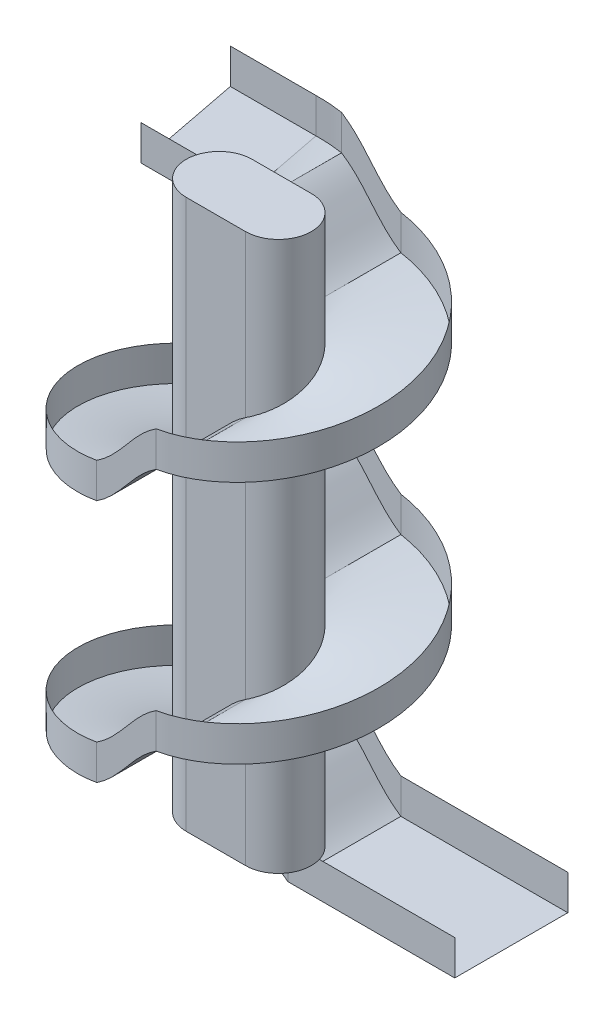
SolidWorks part; units mm, degrees
ref_plane "Front Plane" through (0, 0, 0) normal (0, 0, 1) x (1, 0, 0)
ref_plane "Top Plane" through (0, 0, 0) normal (0, 1, 0) x (1, 0, 0)
ref_plane "Right Plane" through (0, 0, 0) normal (1, 0, 0) x (0, 0, -1)
sketch "Sketch1" plane through (0, 0, 0) normal (0, 1, 0) x (1, 0, 0)
  line L0 (135, 0) -> (-135, 0) construction
  line L1 (135, -150) -> (-135, -150)
  line L2 (135, 150) -> (-135, 150)
  arc A0 (135, -150) -> (135, 150) centre (135, 0) ccw
  arc A1 (-135, 150) -> (-135, -150) centre (-135, 0) ccw
  point P2 (0, 0)
  dimension "D2" = 150
  dimension "D1" = 270
extrude "Boss-Extrude1" add sketch "Sketch1" along normal blind 2500
sketch "Sketch2" plane through (0, 0, 0) normal (0, 1, 0) x (1, 0, 0)
  line L0 (0, 0) -> (208.433, 231.5922)
  point P3 (135, 150)
  point P4 (0, 0)
  point P6 (238.2003, 423.4671)
  point P7 (265.9278, 472.7605)
  point P8 (263.4861, 376.4088)
  point P9 (239.374, 341.9629)
  point P10 (0, 0)
  point P11 (249.6725, 356.675)
  point P12 (247.83, 330.44)
  point P13 (248.2794, 312.6481)
  point P14 (0, 0)
  point P15 (0, 0)
  point P16 (243.7487, 306.9428)
  point P17 (0, 0)
  point P18 (237.7154, 299.3454)
  point P19 (0, 0)
  point P20 (231.8164, 291.917)
  point P21 (221.9692, 279.5168)
  point P22 (189.3881, 238.4887)
  point P23 (199.1628, 250.7976)
  point P24 (208.433, 231.5922)
sketch "Sketch3" plane through (0, 0, 0) normal (0, 0, 1) x (1, 0, 0)
  line L0 (0, 0) -> (0, 2500)
  line L1 (-135, 2500) -> (135, 2500) construction
surface "Surface-Sweep1" parameters "D0"=810
sketch3d "3DSketch1"
  spline S2 degree 3 poles (306.0961, 2771.2923, -1420.1826) (303.4329, 1941.2175, -192.0638) (45.5419, 1783.9163, 168.397) (-154.4548, 1654.0385, 148.8124) (-159.2524, 1650.9168, 148.1057) (-168.7601, 1644.6934, 146.2318) (-173.4702, 1641.5918, 145.0645) (-182.7914, 1635.3918, 142.2662) (-187.4039, 1632.296, 140.6343) (-193.0885, 1628.4007, 138.3012) (-194.2215, 1627.6205, 137.8199) (-196.4793, 1626.0576, 136.8277) (-197.6055, 1625.274, 136.3161) (-200.959, 1622.9277, 134.7424) (-203.1614, 1621.3695, 133.6415) (-209.6688, 1616.7095, 130.1871) (-213.8743, 1613.6221, 127.6821) (-222.0149, 1607.4691, 122.2795) (-225.95, 1604.4034, 119.382) (-233.54, 1598.2778, 113.1982) (-237.1898, 1595.2074, 109.9161) (-242.4361, 1590.5776, 104.707) (-244.1468, 1589.0303, 102.9229) (-247.4896, 1585.9255, 99.2585) (-249.112, 1584.3769, 97.3886) (-253.823, 1579.7491, 91.6811) (-256.7604, 1576.6836, 87.7408) (-262.23, 1570.575, 79.6025) (-264.7631, 1567.5351, 75.4028) (-269.4103, 1561.437, 66.7675) (-271.5254, 1558.3808, 62.3309) (-274.3761, 1553.7736, 55.5012) (-275.2726, 1552.2341, 53.1954) (-276.5349, 1549.9174, 49.6931) (-276.942, 1549.1437, 48.5181) (-277.7247, 1547.6011, 46.1648) (-278.1009, 1546.8311, 44.9852) (-279.9062, 1542.9879, 39.0725) (-281.1092, 1539.9335, 34.2963) (-283.0401, 1533.8488, 24.6629) (-283.767, 1530.8118, 19.8098) (-284.7435, 1524.7215, 10.0479) (-284.9932, 1521.67, 5.138) (-285.0032, 1517.071, -2.2636) (-284.9457, 1515.5343, -4.7369) (-284.7666, 1513.2222, -8.4552) (-284.6914, 1512.4496, -9.6974) (-284.5103, 1510.9082, -12.1737) (-284.4046, 1510.1389, -13.4088) (-284.0422, 1507.8351, -17.1044) (-283.7402, 1506.3045, -19.5555) (-283.0175, 1503.2516, -24.4313) (-282.5967, 1501.7294, -26.8561) (-281.1591, 1497.1615, -34.083) (-279.9672, 1494.1183, -38.8401) (-277.1215, 1488.0205, -48.2235) (-275.4678, 1484.9658, -52.8499) (-272.6374, 1480.363, -59.6828) (-271.6355, 1478.8253, -61.9426) (-270.044, 1476.5118, -65.3042) (-269.4981, 1475.7386, -66.4214) (-268.3802, 1474.1948, -68.6387) (-267.8084, 1473.4244, -69.7386) (-266.0549, 1471.1172, -73.012) (-264.8349, 1469.585, -75.1596) (-262.2978, 1466.5223, -79.381) (-260.9804, 1464.9925, -81.4553) (-256.8845, 1460.4053, -87.5685) (-253.9624, 1457.3497, -91.4981) (-247.744, 1451.2276, -99.0593) (-244.4476, 1448.1612, -102.691) (-239.2228, 1443.5412, -107.9058) (-237.4344, 1441.9977, -109.6052) (-234.6813, 1439.6759, -112.0945) (-233.751, 1438.9001, -112.9149) (-231.8705, 1437.3492, -114.5323) (-230.922, 1436.5748, -115.3277) (-226.1399, 1432.7056, -119.239) (-222.1868, 1429.6211, -122.1572) (-214.0418, 1423.4569, -127.5787) (-209.8498, 1420.3772, -130.082) (-201.2376, 1414.2064, -134.6714) (-196.8174, 1411.1153, -136.7576) (-190.0207, 1406.4576, -139.5662) (-187.7268, 1404.9024, -140.4491) (-183.0876, 1401.7765, -142.1043) (-180.7382, 1400.2035, -142.8778) (-173.6688, 1395.4959, -145.0137) (-168.9139, 1392.3629, -146.1975) (-159.3329, 1386.0902, -148.0937) (-154.5068, 1382.9507, -148.8062) (-147.2229, 1378.2232, -149.5211) (-144.7875, 1376.6443, -149.7003) (12.975, 1274.385, -157.4349) (197.8532, 1159.9741, 75.6966) (-469.0887, -358.7344, 727.2505) knots -1.229861 -1.229861 -1.229861 -1.229861 0.03125 0.03125 0.0625 0.0625 0.09375 0.09375 0.125 0.125 0.132813 0.132813 0.140625 0.140625 0.15625 0.15625 0.1875 0.1875 0.21875 0.21875 0.25 0.25 0.265625 0.265625 0.28125 0.28125 0.3125 0.3125 0.34375 0.34375 0.375 0.375 0.390625 0.390625 0.398438 0.398438 0.40625 0.40625 0.4375 0.4375 0.46875 0.46875 0.5 0.5 0.515625 0.515625 0.523438 0.523438 0.53125 0.53125 0.546875 0.546875 0.5625 0.5625 0.59375 0.59375 0.625 0.625 0.640625 0.640625 0.648438 0.648438 0.65625 0.65625 0.671875 0.671875 0.6875 0.6875 0.71875 0.71875 0.75 0.75 0.765625 0.765625 0.773438 0.773438 0.78125 0.78125 0.8125 0.8125 0.84375 0.84375 0.875 0.875 0.890625 0.890625 0.90625 0.90625 0.9375 0.9375 0.96875 0.96875 0.984375 0.984375 1.978083 1.978083 1.978083 1.978083 only from (-135, 1666.6667, 150) to (-135, 1370.2966, -150)
  spline S3 degree 3 poles (306.0961, 1660.1812, -1420.1826) (303.4329, 830.1063, -192.0638) (45.5419, 672.8052, 168.397) (-154.4548, 542.9274, 148.8124) (-159.2524, 539.8057, 148.1057) (-168.7601, 533.5823, 146.2318) (-173.4702, 530.4807, 145.0645) (-182.7914, 524.2807, 142.2662) (-187.4039, 521.1849, 140.6343) (-193.0885, 517.2896, 138.3012) (-194.2215, 516.5094, 137.8199) (-196.4793, 514.9465, 136.8277) (-197.6055, 514.1629, 136.3161) (-200.959, 511.8166, 134.7424) (-203.1614, 510.2584, 133.6415) (-209.6688, 505.5983, 130.1871) (-213.8743, 502.511, 127.6821) (-222.0149, 496.3579, 122.2795) (-225.95, 493.2923, 119.382) (-233.54, 487.1667, 113.1982) (-237.1898, 484.0963, 109.9161) (-242.4361, 479.4665, 104.707) (-244.1468, 477.9192, 102.9229) (-247.4896, 474.8144, 99.2585) (-249.112, 473.2658, 97.3886) (-253.823, 468.638, 91.6811) (-256.7604, 465.5724, 87.7408) (-262.23, 459.4639, 79.6025) (-264.7631, 456.424, 75.4028) (-269.4103, 450.3259, 66.7675) (-271.5254, 447.2697, 62.3309) (-274.3761, 442.6625, 55.5012) (-275.2726, 441.123, 53.1954) (-276.5349, 438.8063, 49.6931) (-276.942, 438.0326, 48.5181) (-277.7247, 436.49, 46.1648) (-278.1009, 435.72, 44.9852) (-279.9062, 431.8768, 39.0725) (-281.1092, 428.8224, 34.2963) (-283.0401, 422.7376, 24.6629) (-283.767, 419.7007, 19.8098) (-284.7435, 413.6104, 10.0479) (-284.9932, 410.5589, 5.138) (-285.0032, 405.9598, -2.2636) (-284.9457, 404.4232, -4.7369) (-284.7666, 402.1111, -8.4552) (-284.6914, 401.3385, -9.6974) (-284.5103, 399.7971, -12.1737) (-284.4046, 399.0278, -13.4088) (-284.0422, 396.724, -17.1044) (-283.7402, 395.1934, -19.5555) (-283.0175, 392.1405, -24.4313) (-282.5967, 390.6182, -26.8561) (-281.1591, 386.0503, -34.083) (-279.9672, 383.0072, -38.8401) (-277.1215, 376.9094, -48.2235) (-275.4678, 373.8547, -52.8499) (-272.6374, 369.2519, -59.6828) (-271.6355, 367.7142, -61.9426) (-270.044, 365.4007, -65.3042) (-269.4981, 364.6275, -66.4214) (-268.3802, 363.0837, -68.6387) (-267.8084, 362.3133, -69.7386) (-266.0549, 360.0061, -73.012) (-264.8349, 358.4739, -75.1596) (-262.2978, 355.4111, -79.381) (-260.9804, 353.8814, -81.4553) (-256.8845, 349.2942, -87.5685) (-253.9624, 346.2386, -91.4981) (-247.744, 340.1165, -99.0593) (-244.4476, 337.0501, -102.691) (-239.2228, 332.43, -107.9058) (-237.4344, 330.8866, -109.6052) (-234.6813, 328.5648, -112.0945) (-233.751, 327.789, -112.9149) (-231.8705, 326.2381, -114.5323) (-230.922, 325.4637, -115.3277) (-226.1399, 321.5945, -119.239) (-222.1868, 318.51, -122.1572) (-214.0418, 312.3458, -127.5787) (-209.8498, 309.2661, -130.082) (-201.2376, 303.0953, -134.6714) (-196.8174, 300.0042, -136.7576) (-190.0207, 295.3465, -139.5662) (-187.7268, 293.7913, -140.4491) (-183.0876, 290.6653, -142.1043) (-180.7382, 289.0924, -142.8778) (-173.6688, 284.3848, -145.0137) (-168.9139, 281.2518, -146.1975) (-159.3329, 274.9791, -148.0937) (-154.5068, 271.8395, -148.8062) (-147.2229, 267.112, -149.5211) (-144.7875, 265.5332, -149.7003) (12.975, 163.2739, -157.4349) (197.8532, 48.863, 75.6966) (-469.0887, -1469.8455, 727.2505) knots -1.229861 -1.229861 -1.229861 -1.229861 0.03125 0.03125 0.0625 0.0625 0.09375 0.09375 0.125 0.125 0.132813 0.132813 0.140625 0.140625 0.15625 0.15625 0.1875 0.1875 0.21875 0.21875 0.25 0.25 0.265625 0.265625 0.28125 0.28125 0.3125 0.3125 0.34375 0.34375 0.375 0.375 0.390625 0.390625 0.398438 0.398438 0.40625 0.40625 0.4375 0.4375 0.46875 0.46875 0.5 0.5 0.515625 0.515625 0.523438 0.523438 0.53125 0.53125 0.546875 0.546875 0.5625 0.5625 0.59375 0.59375 0.625 0.625 0.640625 0.640625 0.648438 0.648438 0.65625 0.65625 0.671875 0.671875 0.6875 0.6875 0.71875 0.71875 0.75 0.75 0.765625 0.765625 0.773438 0.773438 0.78125 0.78125 0.8125 0.8125 0.84375 0.84375 0.875 0.875 0.890625 0.890625 0.90625 0.90625 0.9375 0.9375 0.96875 0.96875 0.984375 0.984375 1.978083 1.978083 1.978083 1.978083 only from (-135, 555.5556, 150) to (-135, 259.1855, -150)
  spline S4 degree 3 poles (-540.0805, 726.5593, 641.2477) (189.7951, 2276.0753, 80.1304) (14.3209, 2384.6243, -157.3391) (-144.5844, 2487.6238, -149.7127) (-146.974, 2489.1729, -149.5405) (-360.4381, 2627.7053, -129.012) (-535.1485, 2754.3772, 338.8163) (-179.6878, 3597.1923, 1479.3575) knots -16.096892 -16.096892 -16.096892 -16.096892 0.25 0.25 0.5 0.5 22.625823 22.625823 22.625823 22.625823 only from (-135, 2481.4077, -150) to (-163.6075, 2500, -147.2468)
  spline S5 degree 3 poles (-135, 2481.4077, -150) (-137.3992, 2482.9676, -150) (-139.7972, 2484.5208, -149.9424) (-144.5844, 2487.6238, -149.7127) (-146.974, 2489.1729, -149.5405) (-154.129, 2493.8162, -148.8524) (-158.8804, 2496.9066, -148.1652) (-163.6075, 2500, -147.2468) knots 0 0 0 0 0.25 0.25 0.5 0.5 1 1 1 1
  spline S6 degree 3 poles (-135, 555.5556, 150) (-139.9082, 552.3677, 150) (-144.7828, 549.2084, 149.7595) (-154.4548, 542.9274, 148.8124) (-159.2524, 539.8057, 148.1057) (-168.7601, 533.5823, 146.2318) (-173.4702, 530.4807, 145.0645) (-182.7914, 524.2807, 142.2662) (-187.4039, 521.1849, 140.6343) (-193.0885, 517.2896, 138.3012) (-194.2215, 516.5094, 137.8199) (-196.4793, 514.9465, 136.8277) (-197.6055, 514.1629, 136.3161) (-200.959, 511.8166, 134.7424) (-203.1614, 510.2584, 133.6415) (-209.6688, 505.5983, 130.1871) (-213.8743, 502.511, 127.6821) (-222.0149, 496.3579, 122.2795) (-225.95, 493.2923, 119.382) (-233.54, 487.1667, 113.1982) (-237.1898, 484.0963, 109.9161) (-242.4361, 479.4665, 104.707) (-244.1468, 477.9192, 102.9229) (-247.4896, 474.8144, 99.2585) (-249.112, 473.2658, 97.3886) (-253.823, 468.638, 91.6811) (-256.7604, 465.5724, 87.7408) (-262.23, 459.4639, 79.6025) (-264.7631, 456.424, 75.4028) (-269.4103, 450.3259, 66.7675) (-271.5254, 447.2697, 62.3309) (-274.3761, 442.6625, 55.5012) (-275.2726, 441.123, 53.1954) (-276.5349, 438.8063, 49.6931) (-276.942, 438.0326, 48.5181) (-277.7247, 436.49, 46.1648) (-278.1009, 435.72, 44.9852) (-279.9062, 431.8768, 39.0725) (-281.1092, 428.8224, 34.2963) (-283.0401, 422.7376, 24.6629) (-283.767, 419.7007, 19.8098) (-284.7435, 413.6104, 10.0479) (-284.9932, 410.5589, 5.138) (-285.0032, 405.9598, -2.2636) (-284.9457, 404.4232, -4.7369) (-284.7666, 402.1111, -8.4552) (-284.6914, 401.3385, -9.6974) (-284.5103, 399.7971, -12.1737) (-284.4046, 399.0278, -13.4088) (-284.0422, 396.724, -17.1044) (-283.7402, 395.1934, -19.5555) (-283.0175, 392.1405, -24.4313) (-282.5967, 390.6182, -26.8561) (-281.1591, 386.0503, -34.083) (-279.9672, 383.0072, -38.8401) (-277.1215, 376.9094, -48.2235) (-275.4678, 373.8547, -52.8499) (-272.6374, 369.2519, -59.6828) (-271.6355, 367.7142, -61.9426) (-270.044, 365.4007, -65.3042) (-269.4981, 364.6275, -66.4214) (-268.3802, 363.0837, -68.6387) (-267.8084, 362.3133, -69.7386) (-266.0549, 360.0061, -73.012) (-264.8349, 358.4739, -75.1596) (-262.2978, 355.4111, -79.381) (-260.9804, 353.8814, -81.4553) (-256.8845, 349.2942, -87.5685) (-253.9624, 346.2386, -91.4981) (-247.744, 340.1165, -99.0593) (-244.4476, 337.0501, -102.691) (-239.2228, 332.43, -107.9058) (-237.4344, 330.8866, -109.6052) (-234.6813, 328.5648, -112.0945) (-233.751, 327.789, -112.9149) (-231.8705, 326.2381, -114.5323) (-230.922, 325.4637, -115.3277) (-226.1399, 321.5945, -119.239) (-222.1868, 318.51, -122.1572) (-214.0418, 312.3458, -127.5787) (-209.8498, 309.2661, -130.082) (-201.2376, 303.0953, -134.6714) (-196.8174, 300.0042, -136.7576) (-190.0207, 295.3465, -139.5662) (-187.7268, 293.7913, -140.4491) (-183.0876, 290.6653, -142.1043) (-180.7382, 289.0924, -142.8778) (-173.6688, 284.3848, -145.0137) (-168.9139, 281.2518, -146.1975) (-159.3329, 274.9791, -148.0937) (-154.5068, 271.8395, -148.8062) (-147.2229, 267.112, -149.5211) (-144.7875, 265.5332, -149.7003) (-139.903, 262.3671, -149.9398) (-137.4534, 260.7807, -150) (-135, 259.1855, -150) knots 0 0 0 0 0.03125 0.03125 0.0625 0.0625 0.09375 0.09375 0.125 0.125 0.132813 0.132813 0.140625 0.140625 0.15625 0.15625 0.1875 0.1875 0.21875 0.21875 0.25 0.25 0.265625 0.265625 0.28125 0.28125 0.3125 0.3125 0.34375 0.34375 0.375 0.375 0.390625 0.390625 0.398438 0.398438 0.40625 0.40625 0.4375 0.4375 0.46875 0.46875 0.5 0.5 0.515625 0.515625 0.523438 0.523438 0.53125 0.53125 0.546875 0.546875 0.5625 0.5625 0.59375 0.59375 0.625 0.625 0.640625 0.640625 0.648438 0.648438 0.65625 0.65625 0.671875 0.671875 0.6875 0.6875 0.71875 0.71875 0.75 0.75 0.765625 0.765625 0.773438 0.773438 0.78125 0.78125 0.8125 0.8125 0.84375 0.84375 0.875 0.875 0.890625 0.890625 0.90625 0.90625 0.9375 0.9375 0.96875 0.96875 0.984375 0.984375 1 1 1 1
  spline S7 degree 3 poles (-135, 1666.6667, 150) (-139.9082, 1663.4788, 150) (-144.7828, 1660.3196, 149.7595) (-154.4548, 1654.0385, 148.8124) (-159.2524, 1650.9168, 148.1057) (-168.7601, 1644.6934, 146.2318) (-173.4702, 1641.5918, 145.0645) (-182.7914, 1635.3918, 142.2662) (-187.4039, 1632.296, 140.6343) (-193.0885, 1628.4007, 138.3012) (-194.2215, 1627.6205, 137.8199) (-196.4793, 1626.0576, 136.8277) (-197.6055, 1625.274, 136.3161) (-200.959, 1622.9277, 134.7424) (-203.1614, 1621.3695, 133.6415) (-209.6688, 1616.7095, 130.1871) (-213.8743, 1613.6221, 127.6821) (-222.0149, 1607.4691, 122.2795) (-225.95, 1604.4034, 119.382) (-233.54, 1598.2778, 113.1982) (-237.1898, 1595.2074, 109.9161) (-242.4361, 1590.5776, 104.707) (-244.1468, 1589.0303, 102.9229) (-247.4896, 1585.9255, 99.2585) (-249.112, 1584.3769, 97.3886) (-253.823, 1579.7491, 91.6811) (-256.7604, 1576.6836, 87.7408) (-262.23, 1570.575, 79.6025) (-264.7631, 1567.5351, 75.4028) (-269.4103, 1561.437, 66.7675) (-271.5254, 1558.3808, 62.3309) (-274.3761, 1553.7736, 55.5012) (-275.2726, 1552.2341, 53.1954) (-276.5349, 1549.9174, 49.6931) (-276.942, 1549.1437, 48.5181) (-277.7247, 1547.6011, 46.1648) (-278.1009, 1546.8311, 44.9852) (-279.9062, 1542.9879, 39.0725) (-281.1092, 1539.9335, 34.2963) (-283.0401, 1533.8488, 24.6629) (-283.767, 1530.8118, 19.8098) (-284.7435, 1524.7215, 10.0479) (-284.9932, 1521.67, 5.138) (-285.0032, 1517.071, -2.2636) (-284.9457, 1515.5343, -4.7369) (-284.7666, 1513.2222, -8.4552) (-284.6914, 1512.4496, -9.6974) (-284.5103, 1510.9082, -12.1737) (-284.4046, 1510.1389, -13.4088) (-284.0422, 1507.8351, -17.1044) (-283.7402, 1506.3045, -19.5555) (-283.0175, 1503.2516, -24.4313) (-282.5967, 1501.7294, -26.8561) (-281.1591, 1497.1615, -34.083) (-279.9672, 1494.1183, -38.8401) (-277.1215, 1488.0205, -48.2235) (-275.4678, 1484.9658, -52.8499) (-272.6374, 1480.363, -59.6828) (-271.6355, 1478.8253, -61.9426) (-270.044, 1476.5118, -65.3042) (-269.4981, 1475.7386, -66.4214) (-268.3802, 1474.1948, -68.6387) (-267.8084, 1473.4244, -69.7386) (-266.0549, 1471.1172, -73.012) (-264.8349, 1469.585, -75.1596) (-262.2978, 1466.5223, -79.381) (-260.9804, 1464.9925, -81.4553) (-256.8845, 1460.4053, -87.5685) (-253.9624, 1457.3497, -91.4981) (-247.744, 1451.2276, -99.0593) (-244.4476, 1448.1612, -102.691) (-239.2228, 1443.5412, -107.9058) (-237.4344, 1441.9977, -109.6052) (-234.6813, 1439.6759, -112.0945) (-233.751, 1438.9001, -112.9149) (-231.8705, 1437.3492, -114.5323) (-230.922, 1436.5748, -115.3277) (-226.1399, 1432.7056, -119.239) (-222.1868, 1429.6211, -122.1572) (-214.0418, 1423.4569, -127.5787) (-209.8498, 1420.3772, -130.082) (-201.2376, 1414.2064, -134.6714) (-196.8174, 1411.1153, -136.7576) (-190.0207, 1406.4576, -139.5662) (-187.7268, 1404.9024, -140.4491) (-183.0876, 1401.7765, -142.1043) (-180.7382, 1400.2035, -142.8778) (-173.6688, 1395.4959, -145.0137) (-168.9139, 1392.3629, -146.1975) (-159.3329, 1386.0902, -148.0937) (-154.5068, 1382.9507, -148.8062) (-147.2229, 1378.2232, -149.5211) (-144.7875, 1376.6443, -149.7003) (-139.903, 1373.4782, -149.9398) (-137.4534, 1371.8918, -150) (-135, 1370.2966, -150) knots 0 0 0 0 0.03125 0.03125 0.0625 0.0625 0.09375 0.09375 0.125 0.125 0.132813 0.132813 0.140625 0.140625 0.15625 0.15625 0.1875 0.1875 0.21875 0.21875 0.25 0.25 0.265625 0.265625 0.28125 0.28125 0.3125 0.3125 0.34375 0.34375 0.375 0.375 0.390625 0.390625 0.398438 0.398438 0.40625 0.40625 0.4375 0.4375 0.46875 0.46875 0.5 0.5 0.515625 0.515625 0.523438 0.523438 0.53125 0.53125 0.546875 0.546875 0.5625 0.5625 0.59375 0.59375 0.625 0.625 0.640625 0.640625 0.648438 0.648438 0.65625 0.65625 0.671875 0.671875 0.6875 0.6875 0.71875 0.71875 0.75 0.75 0.765625 0.765625 0.773438 0.773438 0.78125 0.78125 0.8125 0.8125 0.84375 0.84375 0.875 0.875 0.890625 0.890625 0.90625 0.90625 0.9375 0.9375 0.96875 0.96875 0.984375 0.984375 1 1 1 1
  spline S10 degree 3 poles (-135, 2481.4077, -150) (-128.353, 2477.0858, -150) (-121.882, 2472.579, -150) (-109.2606, 2463.2287, -150) (-103.1101, 2458.3854, -150) (-94.0902, 2450.9042, -150) (-91.1179, 2448.3744, -150) (-85.2489, 2443.2354, -150) (-82.3505, 2440.628, -150) (-73.7524, 2432.7038, -150) (-68.15, 2427.2848, -150) (-59.8911, 2419.0044, -150) (-57.1614, 2416.2199, -150) (-51.7563, 2410.5936, -150) (-49.0793, 2407.7538, -150) (-41.1102, 2399.1691, -150) (-35.8805, 2393.3586, -150) (-28.102, 2384.5738, -150) (-25.5219, 2381.6322, -150) (-20.3894, 2375.7197, -150) (-15.2811, 2369.7819, -150) (-10.2007, 2363.8147, -150) (-5.1241, 2357.8436, -150) (-2.5864, 2354.8574, -150) (5.0286, 2345.9006, -150) (10.0933, 2339.9172, -150) (17.7349, 2330.988, -150) (20.2895, 2328.0193, -150) (25.4238, 2322.1078, -150) (28.0053, 2319.167, -150) (35.7803, 2310.3758, -150) (41.0094, 2304.5622, -150) (48.9808, 2295.9741, -150) (51.6592, 2293.1334, -150) (57.068, 2287.5058, -150) (59.7984, 2284.7187, -150) (68.0573, 2276.4279, -150) (73.6619, 2271.0027, -150) (82.2676, 2263.0703, -150) (85.1692, 2260.4604, -150) (91.046, 2255.3166, -150) (94.0218, 2252.7834, -150) (103.0486, 2245.2866, -150) (109.2067, 2240.4336, -150) (121.8498, 2231.0658, -150) (128.335, 2226.551, -150) (135, 2222.2222, -150) knots 0 0 0 0 0.0625 0.0625 0.125 0.125 0.15625 0.15625 0.1875 0.1875 0.25 0.25 0.28125 0.28125 0.3125 0.3125 0.375 0.375 0.40625 0.40625 0.4375 0.46875 0.46875 0.5 0.5 0.5625 0.5625 0.59375 0.59375 0.625 0.625 0.6875 0.6875 0.71875 0.71875 0.75 0.75 0.8125 0.8125 0.84375 0.84375 0.875 0.875 0.9375 0.9375 1 1 1 1
  spline S11 degree 3 poles (-135, 1370.2966, -150) (-128.353, 1365.9747, -150) (-121.882, 1361.4678, -150) (-109.2606, 1352.1176, -150) (-103.1101, 1347.2743, -150) (-94.0902, 1339.793, -150) (-91.1179, 1337.2633, -150) (-85.2489, 1332.1242, -150) (-82.3505, 1329.5168, -150) (-73.7524, 1321.5927, -150) (-68.15, 1316.1737, -150) (-59.8911, 1307.8933, -150) (-57.1614, 1305.1088, -150) (-51.7563, 1299.4825, -150) (-49.0793, 1296.6427, -150) (-41.1102, 1288.0579, -150) (-35.8805, 1282.2475, -150) (-28.102, 1273.4627, -150) (-25.5219, 1270.521, -150) (-20.3894, 1264.6086, -150) (-15.2811, 1258.6708, -150) (-10.2007, 1252.7035, -150) (-5.1241, 1246.7325, -150) (-2.5864, 1243.7463, -150) (5.0286, 1234.7895, -150) (10.0933, 1228.8061, -150) (17.7349, 1219.8769, -150) (20.2895, 1216.9082, -150) (25.4238, 1210.9967, -150) (28.0053, 1208.0559, -150) (35.7803, 1199.2646, -150) (41.0094, 1193.4511, -150) (48.9808, 1184.863, -150) (51.6592, 1182.0223, -150) (57.068, 1176.3947, -150) (59.7984, 1173.6076, -150) (68.0573, 1165.3168, -150) (73.6619, 1159.8916, -150) (82.2676, 1151.9592, -150) (85.1692, 1149.3493, -150) (91.046, 1144.2055, -150) (94.0218, 1141.6723, -150) (103.0486, 1134.1755, -150) (109.2067, 1129.3225, -150) (121.8498, 1119.9547, -150) (128.335, 1115.4399, -150) (135, 1111.1111, -150) knots 0 0 0 0 0.0625 0.0625 0.125 0.125 0.15625 0.15625 0.1875 0.1875 0.25 0.25 0.28125 0.28125 0.3125 0.3125 0.375 0.375 0.40625 0.40625 0.4375 0.46875 0.46875 0.5 0.5 0.5625 0.5625 0.59375 0.59375 0.625 0.625 0.6875 0.6875 0.71875 0.71875 0.75 0.75 0.8125 0.8125 0.84375 0.84375 0.875 0.875 0.9375 0.9375 1 1 1 1
  spline S12 degree 3 poles (-135, 259.1855, -150) (-128.353, 254.8636, -150) (-121.882, 250.3567, -150) (-109.2606, 241.0065, -150) (-103.1101, 236.1632, -150) (-94.0902, 228.6819, -150) (-91.1179, 226.1522, -150) (-85.2489, 221.0131, -150) (-82.3505, 218.4057, -150) (-73.7524, 210.4816, -150) (-68.15, 205.0626, -150) (-59.8911, 196.7822, -150) (-57.1614, 193.9977, -150) (-51.7563, 188.3714, -150) (-49.0793, 185.5316, -150) (-41.1102, 176.9468, -150) (-35.8805, 171.1364, -150) (-28.102, 162.3516, -150) (-25.5219, 159.4099, -150) (-20.3894, 153.4975, -150) (-15.2811, 147.5596, -150) (-10.2007, 141.5924, -150) (-5.1241, 135.6213, -150) (-2.5864, 132.6351, -150) (5.0286, 123.6784, -150) (10.0933, 117.695, -150) (17.7349, 108.7658, -150) (20.2895, 105.7971, -150) (25.4238, 99.8856, -150) (28.0053, 96.9447, -150) (35.7803, 88.1535, -150) (41.0094, 82.34, -150) (48.9808, 73.7519, -150) (51.6592, 70.9112, -150) (57.068, 65.2835, -150) (59.7984, 62.4965, -150) (68.0573, 54.2056, -150) (73.6619, 48.7805, -150) (82.2676, 40.8481, -150) (85.1692, 38.2382, -150) (91.046, 33.0944, -150) (94.0218, 30.5612, -150) (103.0486, 23.0644, -150) (109.2067, 18.2114, -150) (121.8498, 8.8436, -150) (128.335, 4.3288, -150) (135, 0, -150) knots 0 0 0 0 0.0625 0.0625 0.125 0.125 0.15625 0.15625 0.1875 0.1875 0.25 0.25 0.28125 0.28125 0.3125 0.3125 0.375 0.375 0.40625 0.40625 0.4375 0.46875 0.46875 0.5 0.5 0.5625 0.5625 0.59375 0.59375 0.625 0.625 0.6875 0.6875 0.71875 0.71875 0.75 0.75 0.8125 0.8125 0.84375 0.84375 0.875 0.875 0.9375 0.9375 1 1 1 1
  spline S13 degree 3 poles (135, 1925.8521, 150) (128.3524, 1921.5299, 150) (121.8809, 1917.0227, 150) (109.2585, 1907.6716, 150) (103.1075, 1902.8278, 150) (94.0869, 1895.3459, 150) (91.1144, 1892.8158, 150) (85.245, 1887.6763, 150) (82.3464, 1885.0687, 150) (73.7477, 1877.1438, 150) (68.1449, 1871.7242, 150) (59.8854, 1863.443, 150) (57.1555, 1860.6582, 150) (51.7501, 1855.0315, 150) (49.0728, 1852.1914, 150) (41.1031, 1843.6058, 150) (35.8731, 1837.7948, 150) (28.094, 1829.0091, 150) (25.5137, 1826.0672, 150) (20.3808, 1820.1542, 150) (15.2721, 1814.2158, 150) (10.1914, 1808.2481, 150) (5.1143, 1802.2765, 150) (2.5763, 1799.29, 150) (-5.0393, 1790.3324, 150) (-10.1037, 1784.3493, 150) (-17.7481, 1775.4171, 150) (-20.3041, 1772.4468, 150) (-25.4432, 1766.5301, 150) (-28.0282, 1763.5854, 150) (-35.8158, 1754.7804, 150) (-41.0568, 1748.9542, 150) (-49.0566, 1740.3377, 150) (-51.7463, 1737.486, 150) (-57.1822, 1731.8328, 150) (-59.9294, 1729.0299, 150) (-68.2332, 1720.6993, 150) (-73.8617, 1715.2567, 150) (-82.4885, 1707.3144, 150) (-85.3948, 1704.7038, 150) (-91.2752, 1699.5642, 150) (-94.2496, 1697.0355, 150) (-103.2639, 1689.5589, 150) (-109.4017, 1684.7288, 150) (-121.9731, 1675.4239, 150) (-128.4065, 1670.9491, 150) (-135, 1666.6667, 150) knots 0 0 0 0 0.0625 0.0625 0.125 0.125 0.15625 0.15625 0.1875 0.1875 0.25 0.25 0.28125 0.28125 0.3125 0.3125 0.375 0.375 0.40625 0.40625 0.4375 0.46875 0.46875 0.5 0.5 0.5625 0.5625 0.59375 0.59375 0.625 0.625 0.6875 0.6875 0.71875 0.71875 0.75 0.75 0.8125 0.8125 0.84375 0.84375 0.875 0.875 0.9375 0.9375 1 1 1 1
  spline S14 degree 3 poles (135, 814.741, 150) (128.3524, 810.4188, 150) (121.8809, 805.9115, 150) (109.2585, 796.5605, 150) (103.1075, 791.7167, 150) (94.0869, 784.2348, 150) (91.1144, 781.7047, 150) (85.245, 776.5652, 150) (82.3464, 773.9576, 150) (73.7477, 766.0326, 150) (68.1449, 760.6131, 150) (59.8854, 752.3319, 150) (57.1555, 749.5471, 150) (51.7501, 743.9203, 150) (49.0728, 741.0803, 150) (41.1031, 732.4947, 150) (35.8731, 726.6837, 150) (28.094, 717.898, 150) (25.5137, 714.9561, 150) (20.3808, 709.0431, 150) (15.2721, 703.1047, 150) (10.1914, 697.137, 150) (5.1143, 691.1654, 150) (2.5763, 688.1789, 150) (-5.0393, 679.2213, 150) (-10.1037, 673.2382, 150) (-17.7481, 664.306, 150) (-20.3041, 661.3357, 150) (-25.4432, 655.4189, 150) (-28.0282, 652.4743, 150) (-35.8158, 643.6693, 150) (-41.0568, 637.8431, 150) (-49.0566, 629.2265, 150) (-51.7463, 626.3748, 150) (-57.1822, 620.7217, 150) (-59.9294, 617.9188, 150) (-68.2332, 609.5882, 150) (-73.8617, 604.1456, 150) (-82.4885, 596.2033, 150) (-85.3948, 593.5927, 150) (-91.2752, 588.4531, 150) (-94.2496, 585.9244, 150) (-103.2639, 578.4477, 150) (-109.4017, 573.6177, 150) (-121.9731, 564.3127, 150) (-128.4065, 559.8379, 150) (-135, 555.5556, 150) knots 0 0 0 0 0.0625 0.0625 0.125 0.125 0.15625 0.15625 0.1875 0.1875 0.25 0.25 0.28125 0.28125 0.3125 0.3125 0.375 0.375 0.40625 0.40625 0.4375 0.46875 0.46875 0.5 0.5 0.5625 0.5625 0.59375 0.59375 0.625 0.625 0.6875 0.6875 0.71875 0.71875 0.75 0.75 0.8125 0.8125 0.84375 0.84375 0.875 0.875 0.9375 0.9375 1 1 1 1
  spline S18 degree 3 poles (-306.0961, 2215.7367, 1420.1826) (-303.4329, 1385.6619, 192.0638) (-45.5419, 1228.3608, -168.397) (154.4548, 1098.483, -148.8124) (159.2524, 1095.3613, -148.1057) (168.7601, 1089.1379, -146.2318) (173.4702, 1086.0362, -145.0645) (182.7914, 1079.8363, -142.2662) (187.4039, 1076.7405, -140.6343) (193.0885, 1072.8451, -138.3012) (194.2215, 1072.0649, -137.8199) (196.4793, 1070.5021, -136.8277) (197.6055, 1069.7184, -136.3161) (200.959, 1067.3721, -134.7424) (203.1614, 1065.814, -133.6415) (209.6688, 1061.1539, -130.1871) (213.8743, 1058.0665, -127.6821) (222.0149, 1051.9135, -122.2795) (225.95, 1048.8479, -119.382) (233.54, 1042.7222, -113.1982) (237.1898, 1039.6518, -109.9161) (242.4361, 1035.0221, -104.707) (244.1468, 1033.4748, -102.9229) (247.4896, 1030.37, -99.2585) (249.112, 1028.8214, -97.3886) (253.823, 1024.1936, -91.6811) (256.7604, 1021.128, -87.7408) (262.23, 1015.0195, -79.6025) (264.7631, 1011.9796, -75.4028) (269.4103, 1005.8814, -66.7675) (271.5254, 1002.8253, -62.3309) (274.3761, 998.2181, -55.5012) (275.2726, 996.6785, -53.1954) (276.5349, 994.3618, -49.6931) (276.942, 993.5882, -48.5181) (277.7247, 992.0455, -46.1648) (278.1009, 991.2756, -44.9852) (279.9062, 987.4323, -39.0725) (281.1092, 984.378, -34.2963) (283.0401, 978.2932, -24.6629) (283.767, 975.2563, -19.8098) (284.7435, 969.166, -10.0479) (284.9932, 966.1145, -5.138) (285.0032, 961.5154, 2.2636) (284.9457, 959.9787, 4.7369) (284.7666, 957.6667, 8.4552) (284.6914, 956.894, 9.6974) (284.5103, 955.3526, 12.1737) (284.4046, 954.5834, 13.4088) (284.0422, 952.2796, 17.1044) (283.7402, 950.749, 19.5555) (283.0175, 947.6961, 24.4313) (282.5967, 946.1738, 26.8561) (281.1591, 941.6059, 34.083) (279.9672, 938.5628, 38.8401) (277.1215, 932.4649, 48.2235) (275.4678, 929.4103, 52.8499) (272.6374, 924.8075, 59.6828) (271.6355, 923.2697, 61.9426) (270.044, 920.9563, 65.3042) (269.4981, 920.183, 66.4214) (268.3802, 918.6393, 68.6387) (267.8084, 917.8689, 69.7386) (266.0549, 915.5617, 73.012) (264.8349, 914.0294, 75.1596) (262.2978, 910.9667, 79.381) (260.9804, 909.437, 81.4553) (256.8845, 904.8497, 87.5685) (253.9624, 901.7941, 91.4981) (247.744, 895.672, 99.0593) (244.4476, 892.6056, 102.691) (239.2228, 887.9856, 107.9058) (237.4344, 886.4422, 109.6052) (234.6813, 884.1203, 112.0945) (233.751, 883.3446, 112.9149) (231.8705, 881.7937, 114.5323) (230.922, 881.0193, 115.3277) (226.1399, 877.1501, 119.239) (222.1868, 874.0656, 122.1572) (214.0418, 867.9013, 127.5787) (209.8498, 864.8217, 130.082) (201.2376, 858.6509, 134.6714) (196.8174, 855.5598, 136.7576) (190.0207, 850.902, 139.5662) (187.7268, 849.3468, 140.4491) (183.0876, 846.2209, 142.1043) (180.7382, 844.648, 142.8778) (173.6688, 839.9403, 145.0137) (168.9139, 836.8073, 146.1975) (159.3329, 830.5347, 148.0937) (154.5068, 827.3951, 148.8062) (147.2229, 822.6676, 149.5211) (144.7875, 821.0887, 149.7003) (-12.975, 718.8294, 157.4349) (-197.8532, 604.4186, -75.6966) (469.0887, -914.2899, -727.2505) knots -1.229861 -1.229861 -1.229861 -1.229861 0.03125 0.03125 0.0625 0.0625 0.09375 0.09375 0.125 0.125 0.132813 0.132813 0.140625 0.140625 0.15625 0.15625 0.1875 0.1875 0.21875 0.21875 0.25 0.25 0.265625 0.265625 0.28125 0.28125 0.3125 0.3125 0.34375 0.34375 0.375 0.375 0.390625 0.390625 0.398437 0.398437 0.40625 0.40625 0.4375 0.4375 0.46875 0.46875 0.5 0.5 0.515625 0.515625 0.523437 0.523437 0.53125 0.53125 0.546875 0.546875 0.5625 0.5625 0.59375 0.59375 0.625 0.625 0.640625 0.640625 0.648437 0.648437 0.65625 0.65625 0.671875 0.671875 0.6875 0.6875 0.71875 0.71875 0.75 0.75 0.765625 0.765625 0.773438 0.773438 0.78125 0.78125 0.8125 0.8125 0.84375 0.84375 0.875 0.875 0.890625 0.890625 0.90625 0.90625 0.9375 0.9375 0.96875 0.96875 0.984375 0.984375 1.978083 1.978083 1.978083 1.978083 only from (135, 1111.1111, -150) to (135, 814.741, 150)
  spline S19 degree 3 poles (-306.0961, 3326.8478, 1420.1826) (-303.4329, 2496.773, 192.0638) (-45.5419, 2339.4719, -168.397) (154.4548, 2209.5941, -148.8124) (159.2524, 2206.4724, -148.1057) (168.7601, 2200.249, -146.2318) (173.4702, 2197.1474, -145.0645) (182.7914, 2190.9474, -142.2662) (187.4039, 2187.8516, -140.6343) (193.0885, 2183.9562, -138.3012) (194.2215, 2183.176, -137.8199) (196.4793, 2181.6132, -136.8277) (197.6055, 2180.8295, -136.3161) (200.959, 2178.4833, -134.7424) (203.1614, 2176.9251, -133.6415) (209.6688, 2172.265, -130.1871) (213.8743, 2169.1776, -127.6821) (222.0149, 2163.0246, -122.2795) (225.95, 2159.959, -119.382) (233.54, 2153.8334, -113.1982) (237.1898, 2150.763, -109.9161) (242.4361, 2146.1332, -104.707) (244.1468, 2144.5859, -102.9229) (247.4896, 2141.4811, -99.2585) (249.112, 2139.9325, -97.3886) (253.823, 2135.3047, -91.6811) (256.7604, 2132.2391, -87.7408) (262.23, 2126.1306, -79.6025) (264.7631, 2123.0907, -75.4028) (269.4103, 2116.9925, -66.7675) (271.5254, 2113.9364, -62.3309) (274.3761, 2109.3292, -55.5012) (275.2726, 2107.7897, -53.1954) (276.5349, 2105.4729, -49.6931) (276.942, 2104.6993, -48.5181) (277.7247, 2103.1566, -46.1648) (278.1009, 2102.3867, -44.9852) (279.9062, 2098.5434, -39.0725) (281.1092, 2095.4891, -34.2963) (283.0401, 2089.4043, -24.6629) (283.767, 2086.3674, -19.8098) (284.7435, 2080.2771, -10.0479) (284.9932, 2077.2256, -5.138) (285.0032, 2072.6265, 2.2636) (284.9457, 2071.0899, 4.7369) (284.7666, 2068.7778, 8.4552) (284.6914, 2068.0051, 9.6974) (284.5103, 2066.4637, 12.1737) (284.4046, 2065.6945, 13.4088) (284.0422, 2063.3907, 17.1044) (283.7402, 2061.8601, 19.5555) (283.0175, 2058.8072, 24.4313) (282.5967, 2057.2849, 26.8561) (281.1591, 2052.717, 34.083) (279.9672, 2049.6739, 38.8401) (277.1215, 2043.576, 48.2235) (275.4678, 2040.5214, 52.8499) (272.6374, 2035.9186, 59.6828) (271.6355, 2034.3808, 61.9426) (270.044, 2032.0674, 65.3042) (269.4981, 2031.2942, 66.4214) (268.3802, 2029.7504, 68.6387) (267.8084, 2028.98, 69.7386) (266.0549, 2026.6728, 73.012) (264.8349, 2025.1406, 75.1596) (262.2978, 2022.0778, 79.381) (260.9804, 2020.5481, 81.4553) (256.8845, 2015.9608, 87.5685) (253.9624, 2012.9052, 91.4981) (247.744, 2006.7832, 99.0593) (244.4476, 2003.7167, 102.691) (239.2228, 1999.0967, 107.9058) (237.4344, 1997.5533, 109.6052) (234.6813, 1995.2314, 112.0945) (233.751, 1994.4557, 112.9149) (231.8705, 1992.9048, 114.5323) (230.922, 1992.1304, 115.3277) (226.1399, 1988.2612, 119.239) (222.1868, 1985.1767, 122.1572) (214.0418, 1979.0124, 127.5787) (209.8498, 1975.9328, 130.082) (201.2376, 1969.762, 134.6714) (196.8174, 1966.6709, 136.7576) (190.0207, 1962.0132, 139.5662) (187.7268, 1960.4579, 140.4491) (183.0876, 1957.332, 142.1043) (180.7382, 1955.7591, 142.8778) (173.6688, 1951.0514, 145.0137) (168.9139, 1947.9184, 146.1975) (159.3329, 1941.6458, 148.0937) (154.5068, 1938.5062, 148.8062) (147.2229, 1933.7787, 149.5211) (144.7875, 1932.1999, 149.7003) (-12.975, 1829.9405, 157.4349) (-197.8532, 1715.5297, -75.6966) (469.0887, 196.8212, -727.2505) knots -1.229861 -1.229861 -1.229861 -1.229861 0.03125 0.03125 0.0625 0.0625 0.09375 0.09375 0.125 0.125 0.132813 0.132813 0.140625 0.140625 0.15625 0.15625 0.1875 0.1875 0.21875 0.21875 0.25 0.25 0.265625 0.265625 0.28125 0.28125 0.3125 0.3125 0.34375 0.34375 0.375 0.375 0.390625 0.390625 0.398438 0.398438 0.40625 0.40625 0.4375 0.4375 0.46875 0.46875 0.5 0.5 0.515625 0.515625 0.523438 0.523438 0.53125 0.53125 0.546875 0.546875 0.5625 0.5625 0.59375 0.59375 0.625 0.625 0.640625 0.640625 0.648438 0.648438 0.65625 0.65625 0.671875 0.671875 0.6875 0.6875 0.71875 0.71875 0.75 0.75 0.765625 0.765625 0.773438 0.773438 0.78125 0.78125 0.8125 0.8125 0.84375 0.84375 0.875 0.875 0.890625 0.890625 0.90625 0.90625 0.9375 0.9375 0.96875 0.96875 0.984375 0.984375 1.978083 1.978083 1.978083 1.978083 only from (135, 2222.2222, -150) to (135, 1925.8521, 150)
  spline S20 degree 3 poles (135, 2222.2222, -150) (139.9082, 2219.0344, -150) (144.7828, 2215.8751, -149.7595) (154.4548, 2209.5941, -148.8124) (159.2524, 2206.4724, -148.1057) (168.7601, 2200.249, -146.2318) (173.4702, 2197.1474, -145.0645) (182.7914, 2190.9474, -142.2662) (187.4039, 2187.8516, -140.6343) (193.0885, 2183.9562, -138.3012) (194.2215, 2183.176, -137.8199) (196.4793, 2181.6132, -136.8277) (197.6055, 2180.8295, -136.3161) (200.959, 2178.4833, -134.7424) (203.1614, 2176.9251, -133.6415) (209.6688, 2172.265, -130.1871) (213.8743, 2169.1776, -127.6821) (222.0149, 2163.0246, -122.2795) (225.95, 2159.959, -119.382) (233.54, 2153.8334, -113.1982) (237.1898, 2150.763, -109.9161) (242.4361, 2146.1332, -104.707) (244.1468, 2144.5859, -102.9229) (247.4896, 2141.4811, -99.2585) (249.112, 2139.9325, -97.3886) (253.823, 2135.3047, -91.6811) (256.7604, 2132.2391, -87.7408) (262.23, 2126.1306, -79.6025) (264.7631, 2123.0907, -75.4028) (269.4103, 2116.9925, -66.7675) (271.5254, 2113.9364, -62.3309) (274.3761, 2109.3292, -55.5012) (275.2726, 2107.7897, -53.1954) (276.5349, 2105.4729, -49.6931) (276.942, 2104.6993, -48.5181) (277.7247, 2103.1566, -46.1648) (278.1009, 2102.3867, -44.9852) (279.9062, 2098.5434, -39.0725) (281.1092, 2095.4891, -34.2963) (283.0401, 2089.4043, -24.6629) (283.767, 2086.3674, -19.8098) (284.7435, 2080.2771, -10.0479) (284.9932, 2077.2256, -5.138) (285.0032, 2072.6265, 2.2636) (284.9457, 2071.0899, 4.7369) (284.7666, 2068.7778, 8.4552) (284.6914, 2068.0051, 9.6974) (284.5103, 2066.4637, 12.1737) (284.4046, 2065.6945, 13.4088) (284.0422, 2063.3907, 17.1044) (283.7402, 2061.8601, 19.5555) (283.0175, 2058.8072, 24.4313) (282.5967, 2057.2849, 26.8561) (281.1591, 2052.717, 34.083) (279.9672, 2049.6739, 38.8401) (277.1215, 2043.576, 48.2235) (275.4678, 2040.5214, 52.8499) (272.6374, 2035.9186, 59.6828) (271.6355, 2034.3808, 61.9426) (270.044, 2032.0674, 65.3042) (269.4981, 2031.2942, 66.4214) (268.3802, 2029.7504, 68.6387) (267.8084, 2028.98, 69.7386) (266.0549, 2026.6728, 73.012) (264.8349, 2025.1406, 75.1596) (262.2978, 2022.0778, 79.381) (260.9804, 2020.5481, 81.4553) (256.8845, 2015.9608, 87.5685) (253.9624, 2012.9052, 91.4981) (247.744, 2006.7832, 99.0593) (244.4476, 2003.7167, 102.691) (239.2228, 1999.0967, 107.9058) (237.4344, 1997.5533, 109.6052) (234.6813, 1995.2314, 112.0945) (233.751, 1994.4557, 112.9149) (231.8705, 1992.9048, 114.5323) (230.922, 1992.1304, 115.3277) (226.1399, 1988.2612, 119.239) (222.1868, 1985.1767, 122.1572) (214.0418, 1979.0124, 127.5787) (209.8498, 1975.9328, 130.082) (201.2376, 1969.762, 134.6714) (196.8174, 1966.6709, 136.7576) (190.0207, 1962.0132, 139.5662) (187.7268, 1960.4579, 140.4491) (183.0876, 1957.332, 142.1043) (180.7382, 1955.7591, 142.8778) (173.6688, 1951.0514, 145.0137) (168.9139, 1947.9184, 146.1975) (159.3329, 1941.6458, 148.0937) (154.5068, 1938.5062, 148.8062) (147.2229, 1933.7787, 149.5211) (144.7875, 1932.1999, 149.7003) (139.903, 1929.0338, 149.9398) (137.4534, 1927.4474, 150) (135, 1925.8521, 150) knots 0 0 0 0 0.03125 0.03125 0.0625 0.0625 0.09375 0.09375 0.125 0.125 0.132813 0.132813 0.140625 0.140625 0.15625 0.15625 0.1875 0.1875 0.21875 0.21875 0.25 0.25 0.265625 0.265625 0.28125 0.28125 0.3125 0.3125 0.34375 0.34375 0.375 0.375 0.390625 0.390625 0.398438 0.398438 0.40625 0.40625 0.4375 0.4375 0.46875 0.46875 0.5 0.5 0.515625 0.515625 0.523438 0.523438 0.53125 0.53125 0.546875 0.546875 0.5625 0.5625 0.59375 0.59375 0.625 0.625 0.640625 0.640625 0.648438 0.648438 0.65625 0.65625 0.671875 0.671875 0.6875 0.6875 0.71875 0.71875 0.75 0.75 0.765625 0.765625 0.773438 0.773438 0.78125 0.78125 0.8125 0.8125 0.84375 0.84375 0.875 0.875 0.890625 0.890625 0.90625 0.90625 0.9375 0.9375 0.96875 0.96875 0.984375 0.984375 1 1 1 1
  spline S21 degree 3 poles (135, 1111.1111, -150) (139.9082, 1107.9233, -150) (144.7828, 1104.764, -149.7595) (154.4548, 1098.483, -148.8124) (159.2524, 1095.3613, -148.1057) (168.7601, 1089.1379, -146.2318) (173.4702, 1086.0362, -145.0645) (182.7914, 1079.8363, -142.2662) (187.4039, 1076.7405, -140.6343) (193.0885, 1072.8451, -138.3012) (194.2215, 1072.0649, -137.8199) (196.4793, 1070.5021, -136.8277) (197.6055, 1069.7184, -136.3161) (200.959, 1067.3721, -134.7424) (203.1614, 1065.814, -133.6415) (209.6688, 1061.1539, -130.1871) (213.8743, 1058.0665, -127.6821) (222.0149, 1051.9135, -122.2795) (225.95, 1048.8479, -119.382) (233.54, 1042.7222, -113.1982) (237.1898, 1039.6518, -109.9161) (242.4361, 1035.0221, -104.707) (244.1468, 1033.4748, -102.9229) (247.4896, 1030.37, -99.2585) (249.112, 1028.8214, -97.3886) (253.823, 1024.1936, -91.6811) (256.7604, 1021.128, -87.7408) (262.23, 1015.0195, -79.6025) (264.7631, 1011.9796, -75.4028) (269.4103, 1005.8814, -66.7675) (271.5254, 1002.8253, -62.3309) (274.3761, 998.2181, -55.5012) (275.2726, 996.6785, -53.1954) (276.5349, 994.3618, -49.6931) (276.942, 993.5882, -48.5181) (277.7247, 992.0455, -46.1648) (278.1009, 991.2756, -44.9852) (279.9062, 987.4323, -39.0725) (281.1092, 984.378, -34.2963) (283.0401, 978.2932, -24.6629) (283.767, 975.2563, -19.8098) (284.7435, 969.166, -10.0479) (284.9932, 966.1145, -5.138) (285.0032, 961.5154, 2.2636) (284.9457, 959.9787, 4.7369) (284.7666, 957.6667, 8.4552) (284.6914, 956.894, 9.6974) (284.5103, 955.3526, 12.1737) (284.4046, 954.5834, 13.4088) (284.0422, 952.2796, 17.1044) (283.7402, 950.749, 19.5555) (283.0175, 947.6961, 24.4313) (282.5967, 946.1738, 26.8561) (281.1591, 941.6059, 34.083) (279.9672, 938.5628, 38.8401) (277.1215, 932.4649, 48.2235) (275.4678, 929.4103, 52.8499) (272.6374, 924.8075, 59.6828) (271.6355, 923.2697, 61.9426) (270.044, 920.9563, 65.3042) (269.4981, 920.183, 66.4214) (268.3802, 918.6393, 68.6387) (267.8084, 917.8689, 69.7386) (266.0549, 915.5617, 73.012) (264.8349, 914.0294, 75.1596) (262.2978, 910.9667, 79.381) (260.9804, 909.437, 81.4553) (256.8845, 904.8497, 87.5685) (253.9624, 901.7941, 91.4981) (247.744, 895.672, 99.0593) (244.4476, 892.6056, 102.691) (239.2228, 887.9856, 107.9058) (237.4344, 886.4422, 109.6052) (234.6813, 884.1203, 112.0945) (233.751, 883.3446, 112.9149) (231.8705, 881.7937, 114.5323) (230.922, 881.0193, 115.3277) (226.1399, 877.1501, 119.239) (222.1868, 874.0656, 122.1572) (214.0418, 867.9013, 127.5787) (209.8498, 864.8217, 130.082) (201.2376, 858.6509, 134.6714) (196.8174, 855.5598, 136.7576) (190.0207, 850.902, 139.5662) (187.7268, 849.3468, 140.4491) (183.0876, 846.2209, 142.1043) (180.7382, 844.648, 142.8778) (173.6688, 839.9403, 145.0137) (168.9139, 836.8073, 146.1975) (159.3329, 830.5347, 148.0937) (154.5068, 827.3951, 148.8062) (147.2229, 822.6676, 149.5211) (144.7875, 821.0887, 149.7003) (139.903, 817.9227, 149.9398) (137.4534, 816.3363, 150) (135, 814.741, 150) knots 0 0 0 0 0.03125 0.03125 0.0625 0.0625 0.09375 0.09375 0.125 0.125 0.132813 0.132813 0.140625 0.140625 0.15625 0.15625 0.1875 0.1875 0.21875 0.21875 0.25 0.25 0.265625 0.265625 0.28125 0.28125 0.3125 0.3125 0.34375 0.34375 0.375 0.375 0.390625 0.390625 0.398437 0.398437 0.40625 0.40625 0.4375 0.4375 0.46875 0.46875 0.5 0.5 0.515625 0.515625 0.523437 0.523437 0.53125 0.53125 0.546875 0.546875 0.5625 0.5625 0.59375 0.59375 0.625 0.625 0.640625 0.640625 0.648437 0.648437 0.65625 0.65625 0.671875 0.671875 0.6875 0.6875 0.71875 0.71875 0.75 0.75 0.765625 0.765625 0.773438 0.773438 0.78125 0.78125 0.8125 0.8125 0.84375 0.84375 0.875 0.875 0.890625 0.890625 0.90625 0.90625 0.9375 0.9375 0.96875 0.96875 0.984375 0.984375 1 1 1 1
  spline S25 degree 3 poles (-1941.9444, -518.1925, -150) (-730.827, 368.9783, -150) (-330.374, 404.8123, -150) (-109.2606, 241.0065, -150) (-103.1101, 236.1632, -150) (-94.0902, 228.6819, -150) (-91.1179, 226.1522, -150) (-85.2489, 221.0131, -150) (-82.3505, 218.4057, -150) (-73.7524, 210.4816, -150) (-68.15, 205.0626, -150) (-59.8911, 196.7822, -150) (-57.1614, 193.9977, -150) (-51.7563, 188.3714, -150) (-49.0793, 185.5316, -150) (-41.1102, 176.9468, -150) (-35.8805, 171.1364, -150) (-28.102, 162.3516, -150) (-25.5219, 159.4099, -150) (-20.3894, 153.4975, -150) (-15.2811, 147.5596, -150) (-10.2007, 141.5924, -150) (-5.1241, 135.6213, -150) (-2.5864, 132.6351, -150) (5.0286, 123.6784, -150) (10.0933, 117.695, -150) (17.7349, 108.7658, -150) (20.2895, 105.7971, -150) (25.4238, 99.8856, -150) (28.0053, 96.9447, -150) (35.7803, 88.1535, -150) (41.0094, 82.34, -150) (48.9808, 73.7519, -150) (51.6592, 70.9112, -150) (57.068, 65.2835, -150) (59.7984, 62.4965, -150) (68.0573, 54.2056, -150) (73.6619, 48.7805, -150) (82.2676, 40.8481, -150) (85.1692, 38.2382, -150) (91.046, 33.0944, -150) (94.0218, 30.5612, -150) (103.0486, 23.0644, -150) (109.2067, 18.2114, -150) (329.2623, -144.8362, -150) (729.9864, -109.8591, -150) (1946.3152, 768.4229, -150) knots -2.064863 -2.064863 -2.064863 -2.064863 0.0625 0.0625 0.125 0.125 0.15625 0.15625 0.1875 0.1875 0.25 0.25 0.28125 0.28125 0.3125 0.3125 0.375 0.375 0.40625 0.40625 0.4375 0.46875 0.46875 0.5 0.5 0.5625 0.5625 0.59375 0.59375 0.625 0.625 0.6875 0.6875 0.71875 0.71875 0.75 0.75 0.8125 0.8125 0.84375 0.84375 0.875 0.875 0.9375 0.9375 3.050639 3.050639 3.050639 3.050639 only from (-135, 259.1855, -150) to (135, 0, -150)
  spline S26 degree 3 poles (-1941.9444, 592.9186, -150) (-730.827, 1480.0894, -150) (-330.374, 1515.9234, -150) (-109.2606, 1352.1176, -150) (-103.1101, 1347.2743, -150) (-94.0902, 1339.793, -150) (-91.1179, 1337.2633, -150) (-85.2489, 1332.1242, -150) (-82.3505, 1329.5168, -150) (-73.7524, 1321.5927, -150) (-68.15, 1316.1737, -150) (-59.8911, 1307.8933, -150) (-57.1614, 1305.1088, -150) (-51.7563, 1299.4825, -150) (-49.0793, 1296.6427, -150) (-41.1102, 1288.0579, -150) (-35.8805, 1282.2475, -150) (-28.102, 1273.4627, -150) (-25.5219, 1270.521, -150) (-20.3894, 1264.6086, -150) (-15.2811, 1258.6708, -150) (-10.2007, 1252.7035, -150) (-5.1241, 1246.7325, -150) (-2.5864, 1243.7463, -150) (5.0286, 1234.7895, -150) (10.0933, 1228.8061, -150) (17.7349, 1219.8769, -150) (20.2895, 1216.9082, -150) (25.4238, 1210.9967, -150) (28.0053, 1208.0559, -150) (35.7803, 1199.2646, -150) (41.0094, 1193.4511, -150) (48.9808, 1184.863, -150) (51.6592, 1182.0223, -150) (57.068, 1176.3947, -150) (59.7984, 1173.6076, -150) (68.0573, 1165.3168, -150) (73.6619, 1159.8916, -150) (82.2676, 1151.9592, -150) (85.1692, 1149.3493, -150) (91.046, 1144.2055, -150) (94.0218, 1141.6723, -150) (103.0486, 1134.1755, -150) (109.2067, 1129.3225, -150) (329.2623, 966.2749, -150) (729.9864, 1001.252, -150) (1946.3152, 1879.534, -150) knots -2.064863 -2.064863 -2.064863 -2.064863 0.0625 0.0625 0.125 0.125 0.15625 0.15625 0.1875 0.1875 0.25 0.25 0.28125 0.28125 0.3125 0.3125 0.375 0.375 0.40625 0.40625 0.4375 0.46875 0.46875 0.5 0.5 0.5625 0.5625 0.59375 0.59375 0.625 0.625 0.6875 0.6875 0.71875 0.71875 0.75 0.75 0.8125 0.8125 0.84375 0.84375 0.875 0.875 0.9375 0.9375 3.050639 3.050639 3.050639 3.050639 only from (-135, 1370.2966, -150) to (135, 1111.1111, -150)
  spline S27 degree 3 poles (-1941.9444, 1704.0297, -150) (-730.827, 2591.2005, -150) (-330.374, 2627.0345, -150) (-109.2606, 2463.2287, -150) (-103.1101, 2458.3854, -150) (-94.0902, 2450.9042, -150) (-91.1179, 2448.3744, -150) (-85.2489, 2443.2354, -150) (-82.3505, 2440.628, -150) (-73.7524, 2432.7038, -150) (-68.15, 2427.2848, -150) (-59.8911, 2419.0044, -150) (-57.1614, 2416.2199, -150) (-51.7563, 2410.5936, -150) (-49.0793, 2407.7538, -150) (-41.1102, 2399.1691, -150) (-35.8805, 2393.3586, -150) (-28.102, 2384.5738, -150) (-25.5219, 2381.6322, -150) (-20.3894, 2375.7197, -150) (-15.2811, 2369.7819, -150) (-10.2007, 2363.8147, -150) (-5.1241, 2357.8436, -150) (-2.5864, 2354.8574, -150) (5.0286, 2345.9006, -150) (10.0933, 2339.9172, -150) (17.7349, 2330.988, -150) (20.2895, 2328.0193, -150) (25.4238, 2322.1078, -150) (28.0053, 2319.167, -150) (35.7803, 2310.3758, -150) (41.0094, 2304.5622, -150) (48.9808, 2295.9741, -150) (51.6592, 2293.1334, -150) (57.068, 2287.5058, -150) (59.7984, 2284.7187, -150) (68.0573, 2276.4279, -150) (73.6619, 2271.0027, -150) (82.2676, 2263.0703, -150) (85.1692, 2260.4604, -150) (91.046, 2255.3166, -150) (94.0218, 2252.7834, -150) (103.0486, 2245.2866, -150) (109.2067, 2240.4336, -150) (329.2623, 2077.386, -150) (729.9864, 2112.3631, -150) (1946.3152, 2990.6451, -150) knots -2.064863 -2.064863 -2.064863 -2.064863 0.0625 0.0625 0.125 0.125 0.15625 0.15625 0.1875 0.1875 0.25 0.25 0.28125 0.28125 0.3125 0.3125 0.375 0.375 0.40625 0.40625 0.4375 0.46875 0.46875 0.5 0.5 0.5625 0.5625 0.59375 0.59375 0.625 0.625 0.6875 0.6875 0.71875 0.71875 0.75 0.75 0.8125 0.8125 0.84375 0.84375 0.875 0.875 0.9375 0.9375 3.050639 3.050639 3.050639 3.050639 only from (-135, 2481.4077, -150) to (135, 2222.2222, -150)
  spline S28 degree 3 poles (1941.9465, 37.3579, 150) (730.8217, 924.5365, 150) (330.3715, 960.3676, 150) (109.2585, 796.5605, 150) (103.1075, 791.7167, 150) (94.0869, 784.2348, 150) (91.1144, 781.7047, 150) (85.245, 776.5652, 150) (82.3464, 773.9576, 150) (73.7477, 766.0326, 150) (68.1449, 760.6131, 150) (59.8854, 752.3319, 150) (57.1555, 749.5471, 150) (51.7501, 743.9203, 150) (49.0728, 741.0803, 150) (41.1031, 732.4947, 150) (35.8731, 726.6837, 150) (28.094, 717.898, 150) (25.5137, 714.9561, 150) (20.3808, 709.0431, 150) (15.2721, 703.1047, 150) (10.1914, 697.137, 150) (5.1143, 691.1654, 150) (2.5763, 688.1789, 150) (-5.0393, 679.2213, 150) (-10.1037, 673.2382, 150) (-17.7481, 664.306, 150) (-20.3041, 661.3357, 150) (-25.4432, 655.4189, 150) (-28.0282, 652.4743, 150) (-35.8158, 643.6693, 150) (-41.0568, 637.8431, 150) (-49.0566, 629.2265, 150) (-51.7463, 626.3748, 150) (-57.1822, 620.7217, 150) (-59.9294, 617.9188, 150) (-68.2332, 609.5882, 150) (-73.8617, 604.1456, 150) (-82.4885, 596.2033, 150) (-85.3948, 593.5927, 150) (-91.2752, 588.4531, 150) (-94.2496, 585.9244, 150) (-103.2639, 578.4477, 150) (-109.4017, 573.6177, 150) (-339.3806, 403.3941, 150) (-750.246, 462.8263, 150) (-1901.5681, 1412.3754, 150) knots -2.064685 -2.064685 -2.064685 -2.064685 0.0625 0.0625 0.125 0.125 0.15625 0.15625 0.1875 0.1875 0.25 0.25 0.28125 0.28125 0.3125 0.3125 0.375 0.375 0.40625 0.40625 0.4375 0.46875 0.46875 0.5 0.5 0.5625 0.5625 0.59375 0.59375 0.625 0.625 0.6875 0.6875 0.71875 0.71875 0.75 0.75 0.8125 0.8125 0.84375 0.84375 0.875 0.875 0.9375 0.9375 3.161743 3.161743 3.161743 3.161743 only from (135, 814.741, 150) to (-135, 555.5556, 150)
  spline S29 degree 3 poles (1941.9465, 1148.469, 150) (730.8217, 2035.6476, 150) (330.3715, 2071.4787, 150) (109.2585, 1907.6716, 150) (103.1075, 1902.8278, 150) (94.0869, 1895.3459, 150) (91.1144, 1892.8158, 150) (85.245, 1887.6763, 150) (82.3464, 1885.0687, 150) (73.7477, 1877.1438, 150) (68.1449, 1871.7242, 150) (59.8854, 1863.443, 150) (57.1555, 1860.6582, 150) (51.7501, 1855.0315, 150) (49.0728, 1852.1914, 150) (41.1031, 1843.6058, 150) (35.8731, 1837.7948, 150) (28.094, 1829.0091, 150) (25.5137, 1826.0672, 150) (20.3808, 1820.1542, 150) (15.2721, 1814.2158, 150) (10.1914, 1808.2481, 150) (5.1143, 1802.2765, 150) (2.5763, 1799.29, 150) (-5.0393, 1790.3324, 150) (-10.1037, 1784.3493, 150) (-17.7481, 1775.4171, 150) (-20.3041, 1772.4468, 150) (-25.4432, 1766.5301, 150) (-28.0282, 1763.5854, 150) (-35.8158, 1754.7804, 150) (-41.0568, 1748.9542, 150) (-49.0566, 1740.3377, 150) (-51.7463, 1737.486, 150) (-57.1822, 1731.8328, 150) (-59.9294, 1729.0299, 150) (-68.2332, 1720.6993, 150) (-73.8617, 1715.2567, 150) (-82.4885, 1707.3144, 150) (-85.3948, 1704.7038, 150) (-91.2752, 1699.5642, 150) (-94.2496, 1697.0355, 150) (-103.2639, 1689.5589, 150) (-109.4017, 1684.7288, 150) (-339.3806, 1514.5052, 150) (-750.246, 1573.9374, 150) (-1901.5681, 2523.4865, 150) knots -2.064685 -2.064685 -2.064685 -2.064685 0.0625 0.0625 0.125 0.125 0.15625 0.15625 0.1875 0.1875 0.25 0.25 0.28125 0.28125 0.3125 0.3125 0.375 0.375 0.40625 0.40625 0.4375 0.46875 0.46875 0.5 0.5 0.5625 0.5625 0.59375 0.59375 0.625 0.625 0.6875 0.6875 0.71875 0.71875 0.75 0.75 0.8125 0.8125 0.84375 0.84375 0.875 0.875 0.9375 0.9375 3.161743 3.161743 3.161743 3.161743 only from (135, 1925.8521, 150) to (-135, 1666.6667, 150)
sketch "Sketch4" plane through (0, 0, 0) normal (1, 0, 0) x (0, 0, -1)
  line L2 (42.6486, 129.5931) -> (42.6486, -29.9206)
  line L3 (42.6486, -29.9206) -> (557.3514, -29.9206)
  line L4 (557.3514, 129.5931) -> (557.3514, -29.9206)
  point P0 (150, 129.5931)
  point P2 (0, 0)
  point P4 (0, 0)
surface "Surface-Sweep2"
other "Ruled Surface1" parameters "D1"=390, "D2"=3
other "Ruled Surface2" parameters "D1"=760, "D2"=3
